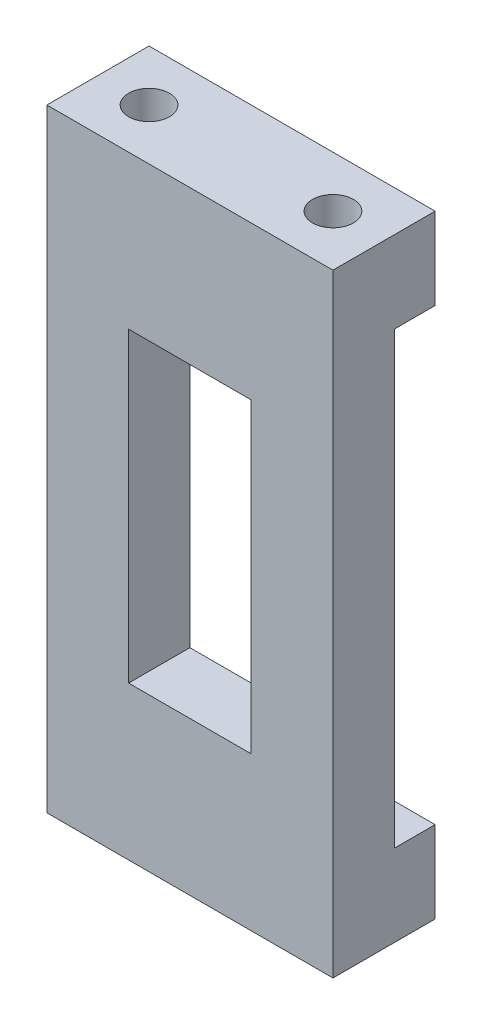
SolidWorks part; units mm, degrees
material "1060 合金"
ref_plane "前视基准面" through (0, 0, 0) normal (0, 0, 1) x (1, 0, 0)
ref_plane "上视基准面" through (0, 0, 0) normal (0, 1, 0) x (1, 0, 0)
ref_plane "右视基准面" through (0, 0, 0) normal (1, 0, 0) x (0, 0, -1)
sketch "草图1" plane through (0, 0, 0) normal (0, 0, 1) x (1, 0, 0)
  line L1 (-14, 30) -> (14, 30)
  line L2 (-14, 30) -> (-14, -30)
  line L3 (-14, -30) -> (14, -30)
  line L4 (14, 30) -> (14, -30)
  line L5 (-6, 15) -> (6, 15)
  line L6 (-6, 15) -> (-6, -15)
  line L7 (-6, -15) -> (6, -15)
  line L8 (6, 15) -> (6, -15)
  point P4 (14, 0)
  point P6 (0, 30)
  point P11 (6, 0)
  point P12 (0, 15)
  dimension "D1" = 60
  dimension "D2" = 28
  dimension "D3" = 8
  dimension "D4" = 15
extrude "凸台-拉伸1" add sketch "草图1" along normal mid plane 6
sketch "草图3" plane through (0, 0, 0) normal (1, 0, 0) x (0, 0, -1)
  line L0 (3, 0) -> (-3, 0) construction
  line L1 (3, -30) -> (3, 30) construction
  line L2 (-3, -30) -> (-3, 30) construction
  line L3 (7, -30) -> (7, -22)
  line L4 (3, 30) -> (7, 30)
  line L5 (3, 30) -> (3, 22)
  line L6 (3, 22) -> (7, 22)
  line L7 (7, 30) -> (7, 22)
  line L8 (3, -22) -> (7, -22)
  line L9 (3, -30) -> (3, -22)
  line L10 (3, -30) -> (7, -30)
  dimension "D1" = 4
  dimension "D2" = 8
extrude "凸台-拉伸2" add sketch "草图3" along normal mid plane 28
sketch "草图2" plane through (0, 30, 0) normal (0, 1, 0) x (1, 0, 0)
  line L0 (0, 3) -> (0, -3) construction
  line L1 (14, 3) -> (-14, 3) construction
  line L2 (14, -3) -> (-14, -3) construction
  circle A0 centre (-9, 2) radius 2
  circle A1 centre (9, 2) radius 2
  dimension "D1" = 4
  dimension "D2" = 18
  dimension "D3" = 5
extrude "切除-拉伸1" cut sketch "草图2" against normal blind 12
mirror "镜向1" about plane through (0, 0, 0) normal (0, 1, 0) of "切除-拉伸1"
